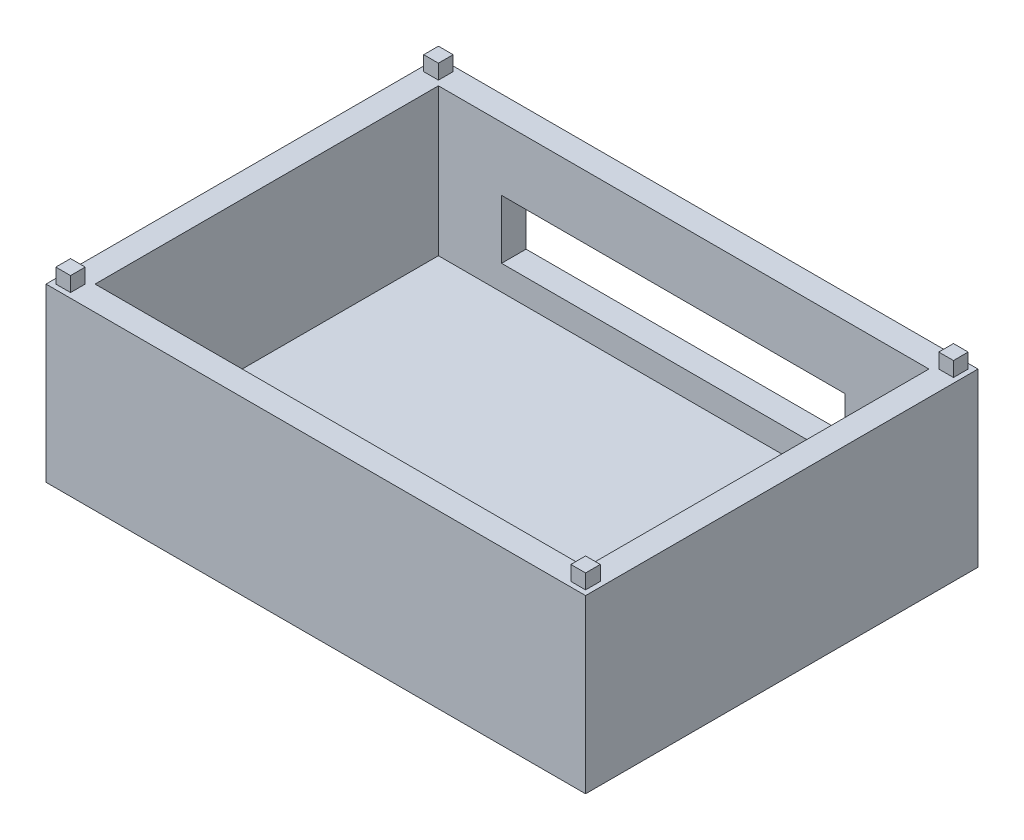
SolidWorks part; units mm, degrees
ref_plane "정면" through (0, 0, 0) normal (0, 0, 1) x (1, 0, 0)
ref_plane "윗면" through (0, 0, 0) normal (0, 1, 0) x (1, 0, 0)
ref_plane "우측면" through (0, 0, 0) normal (1, 0, 0) x (0, 0, -1)
sketch "스케치1" plane through (0, 0, 0) normal (0, 1, 0) x (1, 0, 0)
  line L1 (-55, 40) -> (55, 40)
  line L2 (-55, 40) -> (-55, -40)
  line L3 (-55, -40) -> (55, -40)
  line L4 (55, 40) -> (55, -40)
  line L5 (-55, 40) -> (55, -40) construction
  line L6 (-55, -40) -> (55, 40) construction
  point P0 (0, 0)
extrude "보스-돌출1" add sketch "스케치1" along normal blind 5
sketch "스케치2" plane through (0, 0, 0) normal (0, -1, 0) x (-1, 0, 0)
  line L0 (55, -40) -> (55, -37.5)
  line L1 (55, 40) -> (55, -40) construction
  line L2 (55, -37.5) -> (52.5, -37.5)
  line L3 (55, 40) -> (55, 37.5)
  line L4 (55, 37.5) -> (52.5, 37.5)
  line L5 (-55, -40) -> (-52.5, -40)
  line L6 (55, -40) -> (-55, -40) construction
  line L7 (-52.5, -40) -> (-52.5, -37.5)
  line L8 (-55, 40) -> (-52.5, 40)
  line L9 (-55, 40) -> (55, 40) construction
  line L10 (-52.5, 40) -> (-52.5, 37.5)
sketch "스케치3" plane through (0, 0, 0) normal (0, -1, 0) x (1, 0, 0)
  line L1 (-54.25, 39.25) -> (-50.75, 39.25)
  line L2 (-54.25, 39.25) -> (-54.25, 35.75)
  line L3 (-54.25, 35.75) -> (-50.75, 35.75)
  line L4 (-50.75, 39.25) -> (-50.75, 35.75)
  line L5 (-54.25, 39.25) -> (-50.75, 35.75) construction
  line L6 (-54.25, 35.75) -> (-50.75, 39.25) construction
  line L7 (54.25, 39.25) -> (50.75, 39.25)
  line L8 (54.25, 39.25) -> (54.25, 35.75)
  line L9 (54.25, 35.75) -> (50.75, 35.75)
  line L10 (50.75, 39.25) -> (50.75, 35.75)
  line L11 (54.25, 39.25) -> (50.75, 35.75) construction
  line L12 (54.25, 35.75) -> (50.75, 39.25) construction
  line L13 (-54.25, -35.75) -> (-50.75, -35.75)
  line L14 (-54.25, -35.75) -> (-54.25, -39.25)
  line L15 (-54.25, -39.25) -> (-50.75, -39.25)
  line L16 (-50.75, -35.75) -> (-50.75, -39.25)
  line L17 (-54.25, -35.75) -> (-50.75, -39.25) construction
  line L18 (-54.25, -39.25) -> (-50.75, -35.75) construction
  line L19 (54.25, -39.25) -> (50.75, -39.25)
  line L20 (54.25, -39.25) -> (54.25, -35.75)
  line L21 (54.25, -35.75) -> (50.75, -35.75)
  line L22 (50.75, -39.25) -> (50.75, -35.75)
  line L23 (54.25, -39.25) -> (50.75, -35.75) construction
  line L24 (54.25, -35.75) -> (50.75, -39.25) construction
  point P0 (-52.5, 37.5)
  point P5 (52.5, 37.5)
  point P11 (-52.5, -37.5)
  point P17 (52.5, -37.5)
extrude "컷-돌출1" cut sketch "스케치3" against normal blind 3
sketch "스케치4" plane through (0, 5, 0) normal (0, 1, 0) x (1, 0, 0)
  line L1 (-36.3686, -27.2643) -> (21.6314, -27.2643)
  line L2 (-36.3686, -27.2643) -> (-36.3686, -32.2643)
  line L3 (-36.3686, -32.2643) -> (21.6314, -32.2643)
  line L4 (21.6314, -27.2643) -> (21.6314, -32.2643)
extrude "컷-돌출2" cut sketch "스케치4" against normal blind 5
sketch "스케치5" plane through (0, 5, 0) normal (0, 1, 0) x (1, 0, 0)
  line L1 (-55, 40) -> (55, 40)
  line L2 (-55, 40) -> (-55, -40)
  line L3 (-55, -40) -> (55, -40)
  line L4 (55, 40) -> (55, -40)
  line L5 (-55, 40) -> (55, -40) construction
  line L6 (-55, -40) -> (55, 40) construction
  point P0 (0, 0)
extrude "보스-돌출2" add sketch "스케치5" along normal blind 30
sketch "스케치6" plane through (0, 35, 0) normal (0, 1, 0) x (1, 0, 0)
  line L0 (-55, 40) -> (-50, 40)
  line L1 (-50, 40) -> (-50, 35)
  line L2 (55, 40) -> (55, 35)
  line L3 (55, -40) -> (55, 40) construction
  line L4 (55, 35) -> (50, 35)
  line L5 (-55, -40) -> (-50, -40)
  line L6 (-55, -40) -> (55, -40) construction
  line L7 (-50, -40) -> (-50, -35)
  line L8 (55, -40) -> (55, -35)
  line L9 (55, -35) -> (50, -35)
sketch "스케치7" plane through (0, 35, 0) normal (0, 1, 0) x (1, 0, 0)
  line L1 (-50, 35) -> (50, 35)
  line L2 (-50, 35) -> (-50, -35)
  line L3 (-50, -35) -> (50, -35)
  line L4 (50, 35) -> (50, -35)
  line L5 (-50, 35) -> (50, -35) construction
  line L6 (-50, -35) -> (50, 35) construction
  point P0 (0, 0)
extrude "컷-돌출3" cut sketch "스케치7" against normal blind 30
sketch "스케치8" plane through (0, 35, 0) normal (0, 1, 0) x (1, 0, 0)
  line L1 (-54, 39) -> (-51, 39)
  line L2 (-54, 39) -> (-54, 36)
  line L3 (-54, 36) -> (-51, 36)
  line L4 (-51, 39) -> (-51, 36)
  line L5 (-54, 39) -> (-51, 36) construction
  line L6 (-54, 36) -> (-51, 39) construction
  line L7 (-54, -36) -> (-51, -36)
  line L8 (-54, -36) -> (-54, -39)
  line L9 (-54, -39) -> (-51, -39)
  line L10 (-51, -36) -> (-51, -39)
  line L11 (-54, -36) -> (-51, -39) construction
  line L12 (-54, -39) -> (-51, -36) construction
  line L13 (51, -36) -> (54, -36)
  line L14 (51, -36) -> (51, -39)
  line L15 (51, -39) -> (54, -39)
  line L16 (54, -36) -> (54, -39)
  line L17 (51, -36) -> (54, -39) construction
  line L18 (51, -39) -> (54, -36) construction
  line L19 (51, 39) -> (54, 39)
  line L20 (51, 39) -> (51, 36)
  line L21 (51, 36) -> (54, 36)
  line L22 (54, 39) -> (54, 36)
  line L23 (51, 39) -> (54, 36) construction
  line L24 (51, 36) -> (54, 39) construction
  point P0 (-52.5, 37.5)
  point P5 (-52.5, -37.5)
  point P11 (52.5, -37.5)
  point P17 (52.5, 37.5)
extrude "보스-돌출3" add sketch "스케치8" along normal blind 3
sketch "스케치9" plane through (0, 0, -40) normal (0, 0, -1) x (-1, 0, 0)
  line L1 (-32.8704, 22.0976) -> (37.1296, 22.0976)
  line L2 (-32.8704, 22.0976) -> (-32.8704, 10.0976)
  line L3 (-32.8704, 10.0976) -> (37.1296, 10.0976)
  line L4 (37.1296, 22.0976) -> (37.1296, 10.0976)
extrude "컷-돌출4" cut sketch "스케치9" against normal blind 10
